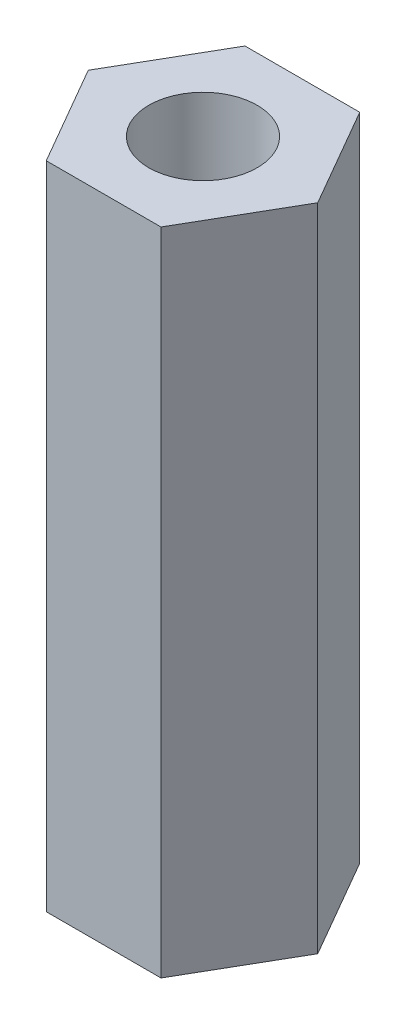
SolidWorks part; units mm, degrees
material "黄铜"
ref_plane "前视基准面" through (0, 0, 0) normal (0, 0, 1) x (1, 0, 0)
ref_plane "上视基准面" through (0, 0, 0) normal (0, 1, 0) x (1, 0, 0)
ref_plane "右视基准面" through (0, 0, 0) normal (1, 0, 0) x (0, 0, -1)
other "Configuration Table"
sketch "草图1" plane through (0, 0, 0) normal (0, 1, 0) x (1, 0, 0)
  line L1 (3.1754, 0) -> (1.5877, 2.75)
  line L2 (1.5877, 2.75) -> (-1.5877, 2.75)
  line L3 (-1.5877, 2.75) -> (-3.1754, 0)
  line L4 (-3.1754, 0) -> (-1.5877, -2.75)
  line L5 (-1.5877, -2.75) -> (1.5877, -2.75)
  line L6 (1.5877, -2.75) -> (3.1754, 0)
  circle A0 centre (0, 0) radius 2.75 construction
  circle A1 centre (0, 0) radius 1.5
  dimension "D1" = 5.5
  dimension "D2" = 3
extrude "凸台-拉伸1" add sketch "草图1" along normal blind 18
